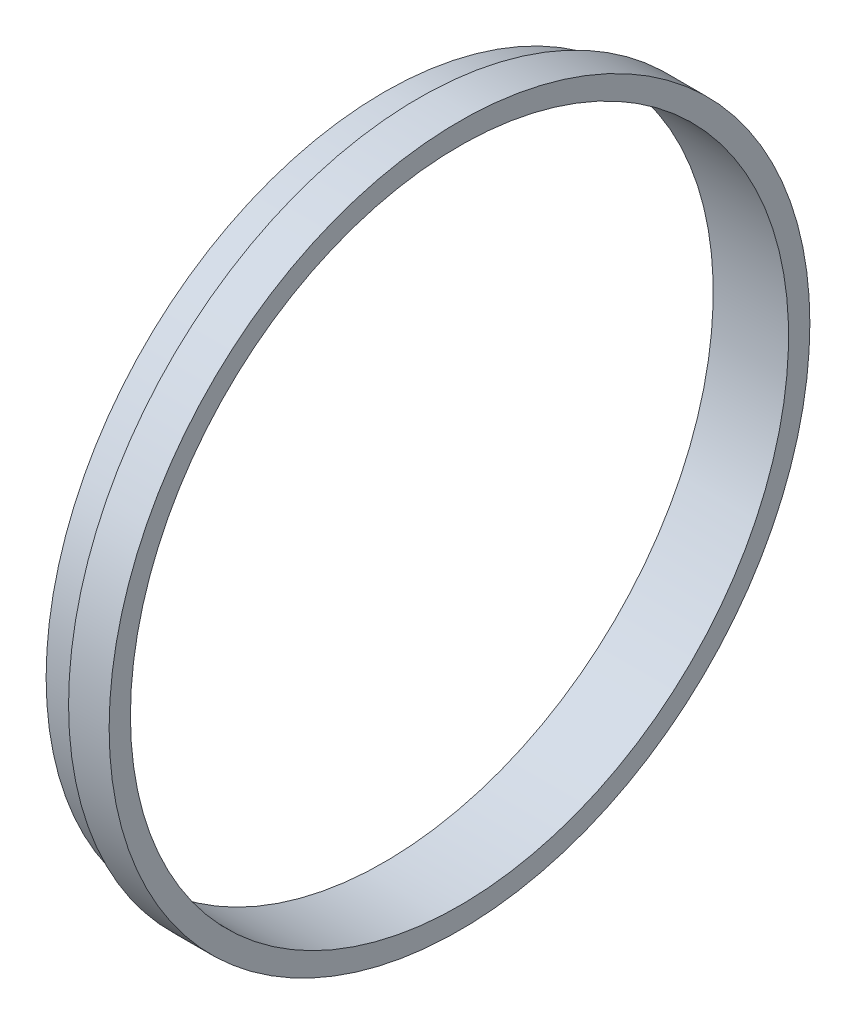
SolidWorks part; units mm, degrees
ref_plane "Front Plane" through (0, 0, 0) normal (0, 0, 1) x (1, 0, 0)
ref_plane "Top Plane" through (0, 0, 0) normal (0, 1, 0) x (1, 0, 0)
ref_plane "Right Plane" through (0, 0, 0) normal (1, 0, 0) x (0, 0, -1)
sketch "OuterDiameter" plane through (0, 0, 0) normal (1, 0, 0) x (0, 0, -1)
  circle A0 centre (0, 0) radius 154.627
  circle A1 centre (0, 0) radius 145.227
  dimension "D1" = 290.454
  dimension "D2" = 9.4
ref_axis "Axis3" through (-72.365, 0, 0) along (1, 0, 0)
sketch "Sketch2" plane through (0, 0, 0) normal (0, 0, 1) x (1, 0, 0)
  line L0 (0, 145.227) -> (33.25, 145.227)
  line L1 (33.25, 145.227) -> (33.25, 154.627)
  line L2 (33.25, 154.627) -> (15.35, 154.627)
  line L3 (15.35, 154.627) -> (15.35, 151.902)
  line L4 (15.35, 151.902) -> (20.15, 151.902)
  line L5 (20.15, 151.902) -> (20.15, 149.177)
  line L6 (20.15, 149.177) -> (0, 149.177)
  line L7 (0, 149.177) -> (0, 145.227)
  point P2 (0, 0)
  dimension "D1" = 3.95
  dimension "D2" = 2.725
  dimension "D3" = 9.4
  dimension "D4" = 20.15
  dimension "D5" = 33.25
  dimension "D6" = 17.9
  dimension "D7" = 145.227
revolve "Revolve1" add sketch "Sketch2" angle 360 about axis through (-72.365, 0, 0) along (1, 0, 0)
